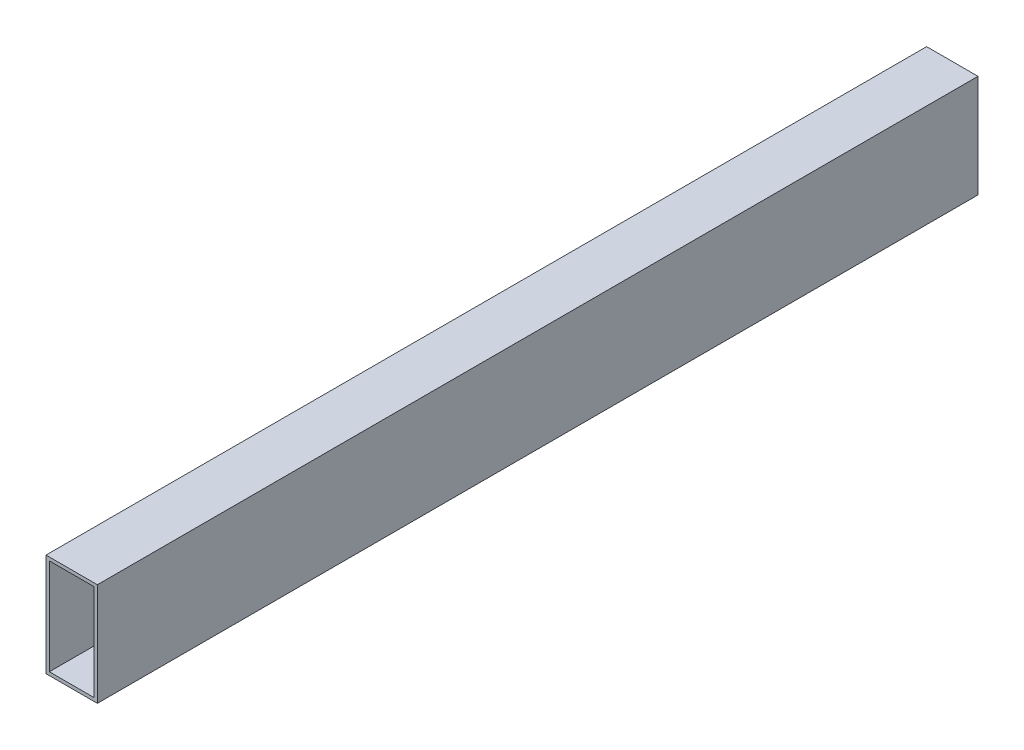
SolidWorks part; units mm, degrees
material "6061 Alloy"
ref_plane "Front Plane" through (0, 0, 0) normal (0, 0, 1) x (1, 0, 0)
ref_plane "Top Plane" through (0, 0, 0) normal (0, 1, 0) x (1, 0, 0)
ref_plane "Right Plane" through (0, 0, 0) normal (1, 0, 0) x (0, 0, -1)
sketch "Sketch1" plane through (0, 0, 0) normal (0, 0, 1) x (1, 0, 0)
  line L1 (-48.4372, -30.1994) -> (-23.0372, -30.1994)
  line L2 (-48.4372, -30.1994) -> (-48.4372, 20.6006)
  line L3 (-48.4372, 20.6006) -> (-23.0372, 20.6006)
  line L4 (-23.0372, -30.1994) -> (-23.0372, 20.6006)
  dimension "D1" = 25.4
  dimension "D2" = 50.8
extrude "Boss-Extrude1" add sketch "Sketch1" along normal blind 435.356
sketch "Sketch2" plane through (0, 0, 435.356) normal (0, 0, 1) x (1, 0, 0)
  line L0 (-48.4372, 20.6006) -> (-48.4372, -30.1994) construction
  line L1 (-46.7862, 18.9496) -> (-24.6882, 18.9496)
  line L2 (-46.7862, 18.9496) -> (-46.7862, -28.5484)
  line L3 (-46.7862, -28.5484) -> (-24.6882, -28.5484)
  line L4 (-24.6882, 18.9496) -> (-24.6882, -28.5484)
  line L5 (-46.7862, 18.9496) -> (-24.6882, -28.5484) construction
  line L6 (-46.7862, -28.5484) -> (-24.6882, 18.9496) construction
  line L7 (-23.0372, -30.1994) -> (-23.0372, 20.6006) construction
  line L8 (-23.0372, 20.6006) -> (-48.4372, 20.6006) construction
  line L9 (-48.4372, -30.1994) -> (-23.0372, -30.1994) construction
  point P0 (-35.7372, -4.7994)
  dimension "D1" = 1.651
  dimension "D2" = 1.651
  dimension "D3" = 1.651
  dimension "D4" = 1.651
extrude "Cut-Extrude1" cut sketch "Sketch2" against normal through all
